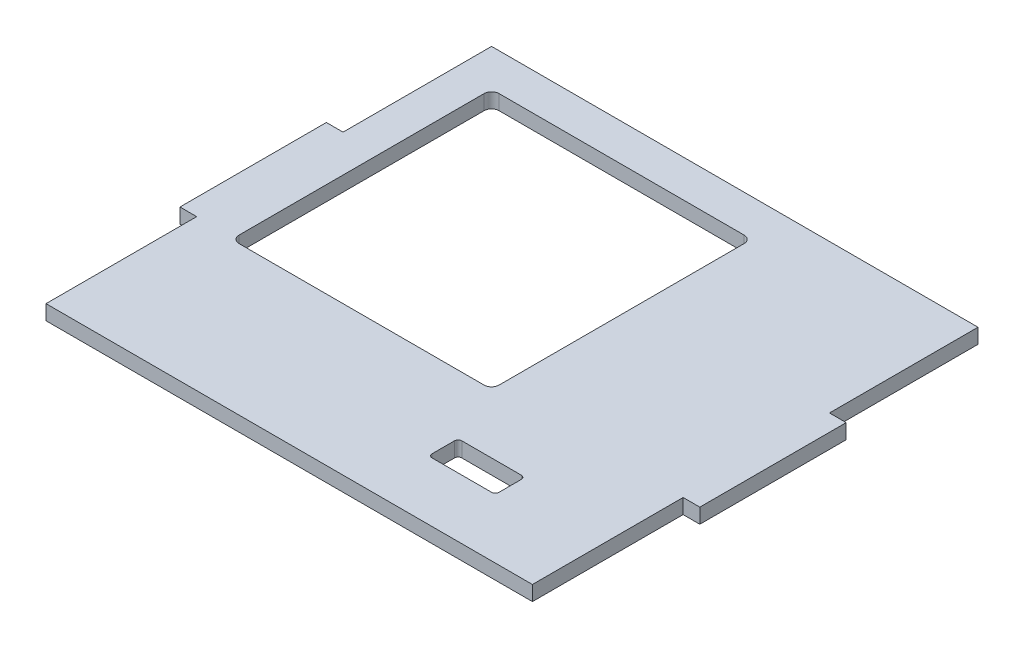
SolidWorks part; units mm, degrees
ref_plane "Front Plane" through (0, 0, 0) normal (0, 0, 1) x (1, 0, 0)
ref_plane "Top Plane" through (0, 0, 0) normal (0, 1, 0) x (1, 0, 0)
ref_plane "Right Plane" through (0, 0, 0) normal (1, 0, 0) x (0, 0, -1)
sketch "Sketch1" plane through (0, 0, 0) normal (0, 1, 0) x (1, 0, 0)
  line L0 (-65.5, 20) -> (-70, 20)
  line L1 (-65.5, -60) -> (65.5, -60)
  line L2 (-65.5, -60) -> (-65.5, -19.4155)
  line L3 (-65.5, 60) -> (65.5, 60)
  line L4 (65.5, -60) -> (65.5, -19.4155)
  line L5 (-65.5, -60) -> (65.5, 60) construction
  line L6 (-65.5, 60) -> (65.5, -60) construction
  line L7 (-70, 20) -> (-70, -19.4155)
  line L8 (-70, -19.4155) -> (-65.5, -19.4155)
  line L9 (-65.5, 20) -> (-65.5, 60)
  line L10 (0, 68.2418) -> (0, -80.8901) construction
  line L11 (70, -19.4155) -> (65.5, -19.4155)
  line L12 (70, 20) -> (70, -19.4155)
  line L13 (65.5, 20) -> (70, 20)
  line L14 (65.5, 20) -> (65.5, 60)
  point P1 (0, 0)
  dimension "D1" = 131
  dimension "D2" = 120
  dimension "D3" = 4.5
  dimension "D4" = 40
  dimension "D5" = 40.5845
extrude "Boss-Extrude1" add sketch "Sketch1" along normal blind 4
sketch "Sketch2" plane through (0, 4, 0) normal (0, 1, 0) x (1, 0, 0)
  line L5 (-53.5, -20) -> (12.5, -20)
  line L6 (22.5, -44) -> (38.5, -44)
  line L7 (21.5, -43) -> (21.5, -37)
  line L8 (22.5, -36) -> (38.5, -36)
  line L9 (39.5, -43) -> (39.5, -37)
  line L10 (21.5, -44) -> (39.5, -36) construction
  line L11 (21.5, -36) -> (39.5, -44) construction
  line L12 (-55.5, -18) -> (-55.5, 48)
  line L13 (-53.5, 50) -> (12.5, 50)
  line L14 (14.5, -18) -> (14.5, 48)
  line L15 (-55.5, -20) -> (14.5, 50) construction
  line L16 (-55.5, 50) -> (14.5, -20) construction
  line L17 (65.5, 60) -> (-65.5, 60) construction
  line L18 (-65.5, 60) -> (-65.5, 20) construction
  arc A2 (21.5, -43) -> (22.5, -44) centre (22.5, -43) ccw
  arc A3 (38.5, -44) -> (39.5, -43) centre (38.5, -43) ccw
  arc A4 (39.5, -37) -> (38.5, -36) centre (38.5, -37) ccw
  arc A5 (21.5, -37) -> (22.5, -36) centre (22.5, -37) cw
  arc A6 (12.5, 50) -> (14.5, 48) centre (12.5, 48) cw
  arc A7 (14.5, -18) -> (12.5, -20) centre (12.5, -18) cw
  arc A8 (-53.5, -20) -> (-55.5, -18) centre (-53.5, -18) cw
  arc A9 (-55.5, 48) -> (-53.5, 50) centre (-53.5, 48) cw
  point P0 (-20.5, 15)
  point P13 (30.5, -40)
  dimension "D5" = 1
  dimension "D6" = 2
  dimension "D1" = 70
  dimension "D2" = 70
  dimension "D3" = 10
  dimension "D4" = 10
extrude "Cut-Extrude1" cut sketch "Sketch2" against normal blind 5
